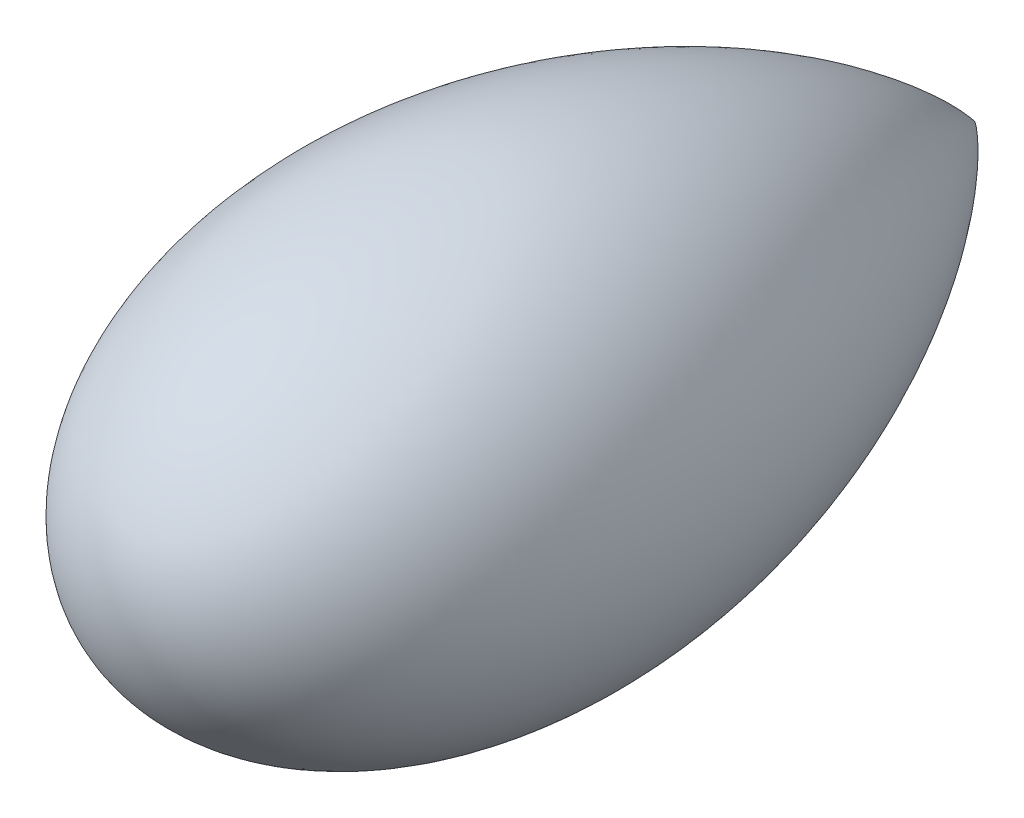
SolidWorks part; units mm, degrees
ref_plane "Front Plane" through (0, 0, 0) normal (0, 0, 1) x (1, 0, 0)
ref_plane "Top Plane" through (0, 0, 0) normal (0, 1, 0) x (1, 0, 0)
ref_plane "Right Plane" through (0, 0, 0) normal (1, 0, 0) x (0, 0, -1)
sketch "Sketch1" plane through (0, 0, 0) normal (0, 1, 0) x (1, 0, 0)
  line L0 (0, 0) -> (0, -21.3227) construction
  line L1 (0, -21.3227) -> (0, 0)
  spline S0 degree 4 poles (-1.9903, -20.77) (-1.9142, -20.8139) (-1.7598, -20.8978) (-1.5226, -21.0109) (-1.196, -21.1346) (-0.9023, -21.2174) (-0.647, -21.2691) (-0.4345, -21.2992) (-0.2569, -21.3153) (-0.052, -21.3244) (0.1311, -21.3227) (0.3673, -21.3081) (0.5551, -21.2829) (0.716, -21.2544) (0.8445, -21.2271) (1.0038, -21.1877) (1.1923, -21.1319) (1.4099, -21.0544) (1.6536, -20.9495) (1.9195, -20.815) (2.2038, -20.6455) (2.5004, -20.4375) (2.8041, -20.1872) (3.1602, -19.8481) (3.55, -19.4043) (3.9513, -18.8437) (4.4366, -17.9906) (4.8915, -16.9018) (5.2563, -15.5735) (5.4763, -14.0156) (5.5228, -12.4409) (5.4133, -10.8698) (5.1614, -9.3156) (4.7774, -7.7887) (4.2688, -6.2989) (3.6403, -4.8555) (2.8946, -3.4689) (2.1426, -2.3228) (1.4261, -1.4022) (0.8511, -0.7688) (0.4626, -0.3871) (0.1959, -0.1524) (0.0663, -0.0495) (0, 0) knots 0 0 0 0 0 0.012733 0.025467 0.038032 0.050597 0.05688 0.063162 0.069445 0.075727 0.085225 0.094723 0.099472 0.104221 0.10897 0.113719 0.123217 0.132715 0.142433 0.15215 0.166397 0.180644 0.194891 0.209138 0.237632 0.266126 0.294619 0.351197 0.408185 0.465173 0.52216 0.579148 0.636135 0.693123 0.750111 0.807098 0.864086 0.921074 0.948543 0.976013 0.988006 1 1 1 1 1 construction
  spline S1 degree 4 poles (0, -21.3227) (0.0606, -21.3227) (0.1805, -21.3196) (0.3673, -21.3081) (0.5551, -21.2829) (0.716, -21.2544) (0.8445, -21.2271) (1.0038, -21.1877) (1.1923, -21.1319) (1.4099, -21.0544) (1.6536, -20.9495) (1.9195, -20.815) (2.2038, -20.6455) (2.5004, -20.4375) (2.8041, -20.1872) (3.1602, -19.8481) (3.55, -19.4043) (3.9513, -18.8437) (4.4366, -17.9906) (4.8915, -16.9018) (5.2563, -15.5735) (5.4763, -14.0156) (5.5228, -12.4409) (5.4133, -10.8698) (5.1614, -9.3156) (4.7774, -7.7887) (4.2688, -6.2989) (3.6403, -4.8555) (2.8946, -3.4689) (2.1426, -2.3228) (1.4261, -1.4022) (0.8511, -0.7688) (0.4626, -0.3871) (0.1959, -0.1524) (0.0663, -0.0495) (0, 0) knots 0.075727 0.075727 0.075727 0.075727 0.075727 0.085225 0.094723 0.099472 0.104221 0.10897 0.113719 0.123217 0.132715 0.142433 0.15215 0.166397 0.180644 0.194891 0.209138 0.237632 0.266126 0.294619 0.351197 0.408185 0.465173 0.52216 0.579148 0.636135 0.693123 0.750111 0.807098 0.864086 0.921074 0.948543 0.976013 0.988006 1 1 1 1 1
revolve "Revolve2" add sketch "Sketch1" angle 360 about L0
